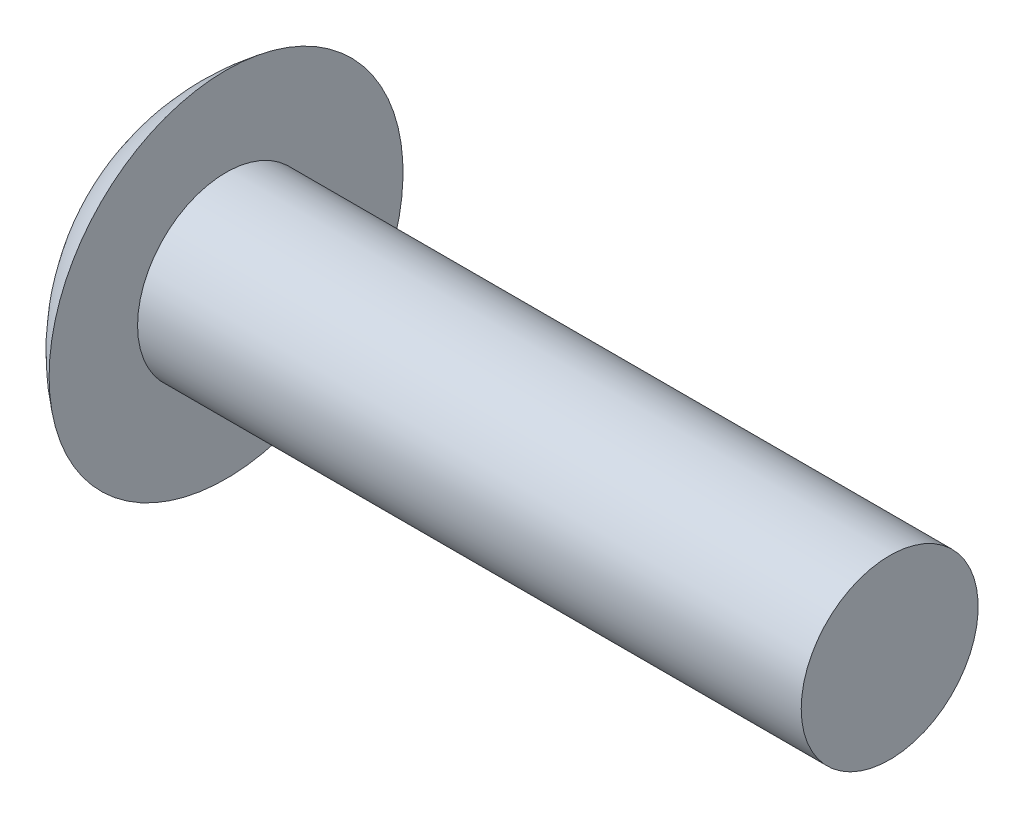
SolidWorks part; units mm, degrees
ref_plane "Front Plane" through (0, 0, 0) normal (0, 0, 1) x (1, 0, 0)
ref_plane "Top Plane" through (0, 0, 0) normal (0, 1, 0) x (1, 0, 0)
ref_plane "Right Plane" through (0, 0, 0) normal (1, 0, 0) x (0, 0, -1)
sketch "Sketch1" plane through (0, 0, 0) normal (0, 0, 1) x (1, 0, 0)
  line L0 (0, 0) -> (17, 0)
  line L1 (17, 0) -> (17, 2)
  line L2 (17, 2) -> (2, 2)
  line L3 (2, 2) -> (2, 4)
  arc A0 (0, 0) -> (2, 4) centre (5, 0) cw
  dimension "D1" = 2
  dimension "D2" = 2
  dimension "D3" = 2
  dimension "D4" = 17
revolve "Revolve1" add sketch "Sketch1" angle 360 about L0
